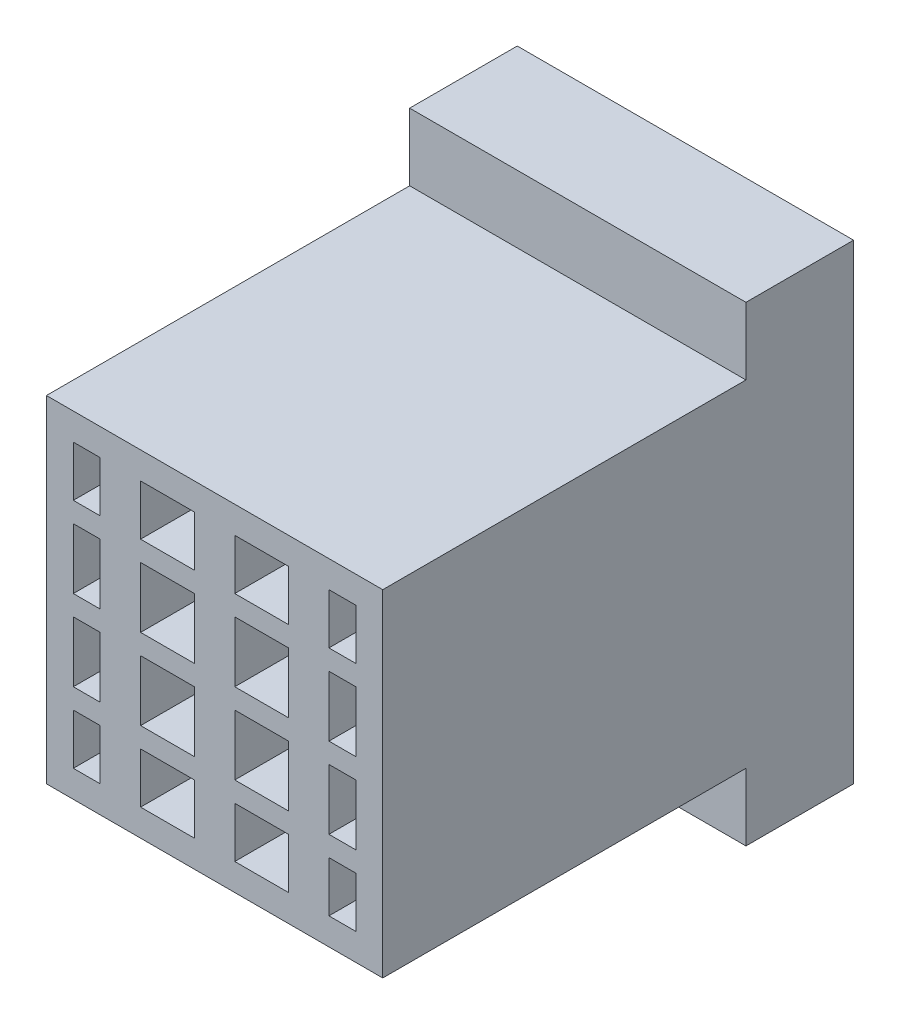
SolidWorks part; units mm, degrees
ref_plane "前视基准面" through (0, 0, 0) normal (0, 0, 1) x (1, 0, 0)
ref_plane "上视基准面" through (0, 0, 0) normal (0, 1, 0) x (1, 0, 0)
ref_plane "右视基准面" through (0, 0, 0) normal (1, 0, 0) x (0, 0, -1)
sketch "草图8" plane through (0, 0, 0) normal (0, 0, 1) x (1, 0, 0)
  line L0 (0, 7.8741) -> (0, -9.2542) construction
  line L1 (-12.5, -12.5) -> (12.5, -12.5)
  line L2 (-12.5, -12.5) -> (-12.5, 12.5)
  line L3 (-12.5, 12.5) -> (12.5, 12.5)
  line L4 (12.5, -12.5) -> (12.5, 12.5)
  line L5 (-12.5, -12.5) -> (12.5, 12.5) construction
  line L6 (-12.5, 12.5) -> (12.5, -12.5) construction
  line L7 (-16.0619, 0) -> (15.5648, 0) construction
  line L8 (-3.5, 7.8741) -> (-3.5, -9.2542) construction
  line L9 (-9.5, 7.8741) -> (-9.5, -9.2542) construction
  line L10 (5.5, 10.5) -> (1.5, 10.5)
  line L15 (-5.5, -10.5) -> (-1.5, -10.5)
  line L20 (-5.5, -10.5) -> (-5.5, 10.5)
  line L21 (-5.5, 10.5) -> (-1.5, 10.5)
  line L26 (-1.5, -10.5) -> (-1.5, 10.5)
  line L27 (-5.5, -10.5) -> (-1.5, 10.5) construction
  line L28 (-5.5, 10.5) -> (-1.5, -10.5) construction
  line L29 (-10.5, -10.5) -> (-8.5, -10.5)
  line L30 (-10.5, -10.5) -> (-10.5, 10.5)
  line L31 (-10.5, 10.5) -> (-8.5, 10.5)
  line L32 (-8.5, -10.5) -> (-8.5, 10.5)
  line L33 (-10.5, -10.5) -> (-8.5, 10.5) construction
  line L34 (-10.5, 10.5) -> (-8.5, -10.5) construction
  line L35 (1.5, -10.5) -> (1.5, 10.5)
  line L36 (5.5, -10.5) -> (1.5, -10.5)
  line L37 (5.5, -10.5) -> (5.5, 10.5)
  line L38 (10.5, 10.5) -> (8.5, 10.5)
  line L39 (8.5, -10.5) -> (8.5, 10.5)
  line L40 (10.5, -10.5) -> (8.5, -10.5)
  line L41 (10.5, -10.5) -> (10.5, 10.5)
  point P0 (0, 0)
  point P14 (-7, 0)
  point P15 (-3.5, 0)
  point P17 (-3, 0)
  point P21 (-9.5, 0)
  point P22 (-9, 0)
  dimension "D1" = 3.5
  dimension "D2" = 6
extrude "凸台-拉伸7" add sketch "草图8" along normal blind 25
sketch "草图9" plane through (0, 0, 0) normal (0, 0, -1) x (-1, 0, 0)
  line L1 (-12.5, -12.5) -> (12.5, -12.5)
  line L2 (-12.5, -12.5) -> (-12.5, 12.5)
  line L3 (-12.5, 12.5) -> (12.5, 12.5)
  line L4 (12.5, -12.5) -> (12.5, 12.5)
  line L5 (-12.5, -12.5) -> (12.5, 12.5) construction
  line L6 (-12.5, 12.5) -> (12.5, -12.5) construction
  point P0 (0, 0)
extrude "凸台-拉伸8" add sketch "草图9" along normal blind 2
sketch "草图11" plane through (0, 0, -2) normal (0, 0, -1) x (-1, 0, 0)
  line L5 (-12.5, -17.5) -> (12.5, -17.5)
  line L6 (-12.5, -17.5) -> (-12.5, 17.5)
  line L7 (-12.5, 17.5) -> (12.5, 17.5)
  line L8 (12.5, -17.5) -> (12.5, 17.5)
  line L9 (-12.5, -17.5) -> (12.5, 17.5) construction
  line L10 (-12.5, 17.5) -> (12.5, -17.5) construction
  point P0 (0, 0)
extrude "凸台-拉伸9" add sketch "草图11" along normal blind 6
sketch "草图12" plane through (0, 0, -8) normal (0, 0, -1) x (-1, 0, 0)
  line L1 (-10.5, -15) -> (10.5, -15)
  line L2 (-10.5, -15) -> (-10.5, 15)
  line L3 (-10.5, 15) -> (10.5, 15)
  line L4 (10.5, -15) -> (10.5, 15)
  line L5 (-10.5, -15) -> (10.5, 15) construction
  line L6 (-10.5, 15) -> (10.5, -15) construction
  point P0 (0, 0)
extrude "切除-拉伸1" cut sketch "草图12" against normal blind 4
sketch "草图14" plane through (0, 0, 25) normal (0, 0, 1) x (1, 0, 0)
  line L0 (-16.6961, 0) -> (20.7273, 0) construction
  line L1 (-12.5, 12.5) -> (-12.5, -12.5) construction
  line L2 (12.5, -0.75) -> (-12.5, -0.75)
  line L3 (12.5, -0.75) -> (12.5, 0.75)
  line L4 (12.5, 0.75) -> (-12.5, 0.75)
  line L5 (-12.5, -0.75) -> (-12.5, 0.75)
  line L6 (12.5, -0.75) -> (-12.5, 0.75) construction
  line L7 (12.5, 0.75) -> (-12.5, -0.75) construction
  line L12 (12.5, 5.25) -> (-12.5, 5.25)
  line L13 (12.5, 5.25) -> (12.5, 6.75)
  line L14 (12.5, 6.75) -> (-12.5, 6.75)
  line L15 (-12.5, 5.25) -> (-12.5, 6.75)
  line L16 (12.5, 5.25) -> (-12.5, 6.75) construction
  line L17 (12.5, 6.75) -> (-12.5, 5.25) construction
  line L18 (12.5, -6.75) -> (-12.5, -5.25) construction
  line L19 (12.5, -5.25) -> (-12.5, -6.75) construction
  line L20 (-12.5, -5.25) -> (-12.5, -6.75)
  line L21 (12.5, -6.75) -> (-12.5, -6.75)
  line L22 (12.5, -5.25) -> (12.5, -6.75)
  line L23 (12.5, -5.25) -> (-12.5, -5.25)
  point P3 (0, 0)
  point P11 (0, 6)
  point P19 (0, -6)
  dimension "D1" = 2
extrude "凸台-拉伸11" add sketch "草图14" against normal blind 25
sketch "草图15" plane through (0, 0, -8) normal (0, 0, -1) x (-1, 0, 0)
  line L1 (-12.5, -17.5) -> (12.5, -17.5)
  line L2 (-12.5, -17.5) -> (-12.5, 17.5)
  line L3 (-12.5, 17.5) -> (12.5, 17.5)
  line L4 (12.5, -17.5) -> (12.5, 17.5)
  line L5 (-12.5, -17.5) -> (12.5, 17.5) construction
  line L6 (-12.5, 17.5) -> (12.5, -17.5) construction
  point P0 (0, 0)
extrude "凸台-拉伸12" add sketch "草图15" along normal blind 2
sketch "草图16" plane through (12.5, 0, 0) normal (1, 0, 0) x (0, 0, -1)
  line L0 (-20, 12.5) -> (-20, -12.5)
  line L1 (-25, 12.5) -> (2, 12.5) construction
  line L2 (-25, -12.5) -> (2, -12.5) construction
  line L3 (-25, -12.5) -> (-25, 12.5) construction
  line L4 (-25, -5.8618) -> (10, -5.8618)
  line L5 (10, 17.5) -> (10, -17.5) construction
  line L6 (-25, 5.9976) -> (10, 5.9976)
  dimension "D1" = 5
sketch "草图17" plane through (-12.5, 0, 0) normal (-1, 0, 0) x (0, 0, 1)
  line L0 (20, 12.5) -> (20, -12.5)
  line L1 (25, 5.9976) -> (-10, 5.9976)
  line L2 (25, -5.8618) -> (-10, -5.8618)
